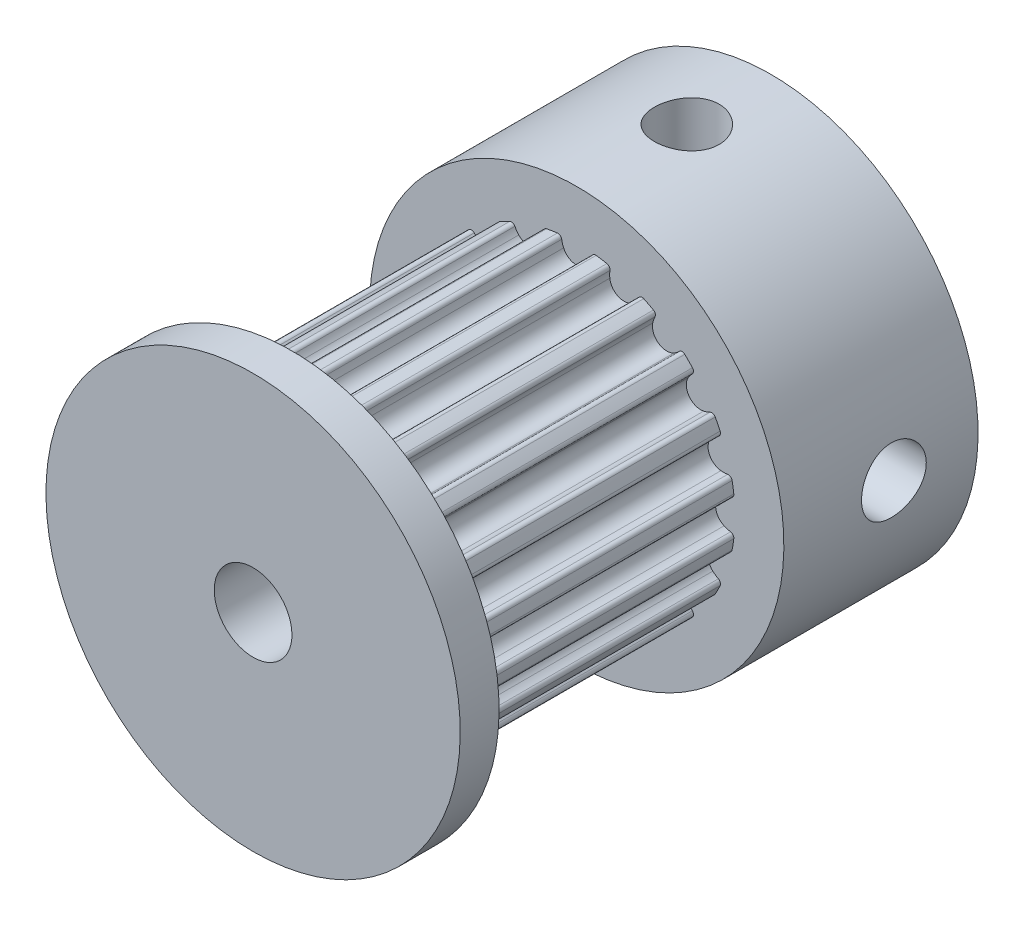
SolidWorks part; units mm, degrees
ref_plane "Front Plane" through (0, 0, 0) normal (1, 0, 0) x (0, 1, 0)
ref_plane "Top Plane" through (0, 0, 0) normal (0, 0, 1) x (0, 1, 0)
ref_plane "Right Plane" through (0, 0, 0) normal (0, 1, 0) x (-1, 0, 0)
other "Configuration Table"
sketch "Sketch1" plane through (0, 0, 0) normal (1, 0, 0) x (0, 1, 0)
  line L0 (0, 0) -> (0, -14) construction
  line L1 (1.5, -14) -> (8, -14)
  line L2 (8, -14) -> (8, -12.5)
  line L3 (8, -12.5) -> (6.1122, -12.5)
  line L4 (6.1122, -12.5) -> (6.1122, -1.5)
  line L5 (6.1122, -1.5) -> (8, -1.5)
  line L6 (8, -1.5) -> (8, 0)
  line L7 (8, 0) -> (1.5, 0)
  line L8 (1.5, 0) -> (1.5, -14)
  dimension "beltWidth" = 11
  dimension "flangeThickness" = 1.5
  dimension "outerDiameter" = 16
  dimension "toothedDiameter" = 12.2244
  dimension "boreDiameter" = 3
revolve "Revolve1" add sketch "Sketch1" angle 360 about L0
sketch "Sketch2" plane through (0, 0, -12.5) normal (0, 0, 1) x (1, 0, 0)
  line L0 (0, 0) -> (0, 6.1122) construction
  circle A0 centre (0, 0) radius 6.1122 construction
  circle A1 centre (0, 0) radius 6.1122 construction
  arc A2 (-0.7477, 6.0663) -> (-0.5812, 5.9411) centre (-0.7293, 5.9174) cw
  arc A3 (-0.5812, 5.9411) -> (-0.5067, 5.6909) centre (0.4063, 6.0987) ccw
  arc A4 (-0.5067, 5.6909) -> (0.5067, 5.6909) centre (0, 5.9172) ccw
  arc A5 (0.7477, 6.0663) -> (0.5812, 5.9411) centre (0.7293, 5.9174) ccw
  arc A6 (0.5812, 5.9411) -> (0.5067, 5.6909) centre (-0.4063, 6.0987) cw
  arc A7 (-0.7477, 6.0663) -> (0.7477, 6.0663) centre (0, 0) cw
  point P10 (0, 5.3622)
  point P15 (-0.5522, 5.8135)
  point P19 (0.5522, 5.8135)
  dimension "R3" = 0.555
  dimension "R1" = 0.15
  dimension "R2" = 1
  dimension "h" = 0.75
extrude "Cut-Extrude1" cut sketch "Sketch2" along normal up to surface (11 mm away) contours A7 A5 A6 A4 A3 A2 up to face at (0, -8, -1.5)
pattern_circular "CirPattern1" count 20 over 360 about axis through (0, 0, 0) along (0, 0, 1) of "Cut-Extrude1"
sketch "Sketch3" plane through (0, 0, -14) normal (0, 0, -1) x (1, 0, 0)
  circle A0 centre (0, 0) radius 8
  circle A1 centre (0, 0) radius 1.5 construction
  circle A2 centre (0, 0) radius 1.5
  dimension "stubDiameter" = 16
extrude "Boss-Extrude1" add sketch "Sketch3" along normal blind 6
sketch "Sketch4" plane through (0, 0, 0) normal (1, 0, 0) x (0, 1, 0)
  point P0 (0, -16.75)
  dimension "holeDistance" = 16.75
hole_wizard "M3 Tapped Hole1" positions "Sketch4" profile "Sketch5" tap size "M3" standard "ISO"
sketch "Sketch5" plane through (0, 0, -16.75) normal (0, 1, 0) x (0, 0, 1)
  line L0 (0, 0) -> (0, 8)
  line L1 (0, 8) -> (1.25, 8)
  line L2 (1.25, 8) -> (1.25, 0)
  line L5 (1.25, 0) -> (0, 0)
  line L11 (0, -6.35) -> (0, 107.95) construction
  dimension "Thru Tap Drill Dia." = 2.5
  dimension "Thru Tap Drill Depth" = 8
cosmetic thread "Hole Thread1" parameters "D2"=3
pattern_circular "CirPattern2" count 2 every 90 about axis through (0, 0, 0) along (0, 0, 1) of "M3 Tapped Hole1"
cosmetic thread "Hole Thread2" parameters "D2"=3
sketch "Sketch6" plane through (0, 0, -12.5) normal (0, 0, 1) x (1, 0, 0)
  circle A0 centre (0, 0) radius 6.7422
  dimension "beltOutside" = 13.4844
